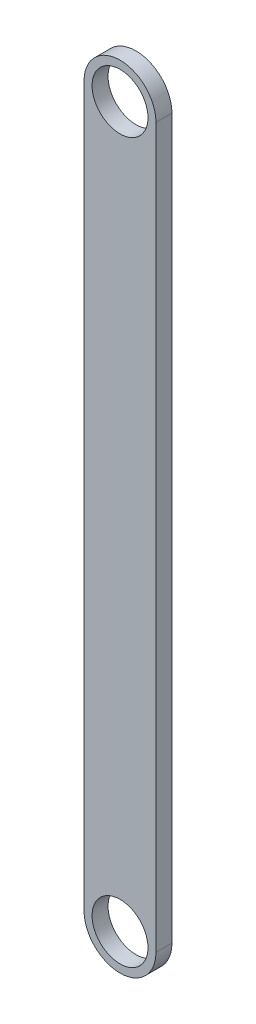
SolidWorks part; units mm, degrees
ref_plane "Front Plane" through (0, 0, 0) normal (0, 0, 1) x (1, 0, 0)
ref_plane "Top Plane" through (0, 0, 0) normal (0, 1, 0) x (1, 0, 0)
ref_plane "Right Plane" through (0, 0, 0) normal (1, 0, 0) x (0, 0, -1)
sketch "Sketch1" plane through (0, 0, 0) normal (0, 0, 1) x (1, 0, 0)
  line L0 (0, -1143) -> (0, 1143) construction
  line L1 (-114.3, -1143) -> (-114.3, 1143)
  line L2 (114.3, -1143) -> (114.3, 1143)
  circle A0 centre (0, 1143) radius 88.9
  circle A1 centre (0, -1143) radius 88.9
  arc A2 (114.3, 1143) -> (-114.3, 1143) centre (0, 1143) ccw
  arc A3 (-114.3, -1143) -> (114.3, -1143) centre (0, -1143) ccw
  point P4 (0, 0)
  dimension "D3" = 177.8
  dimension "D4" = 177.8
  dimension "D5" = 228.6
  dimension "D6" = 228.6
  dimension "D1" = 1143
  dimension "D2" = 2286
extrude "Boss-Extrude1" add sketch "Sketch1" along normal mid plane 50.8
